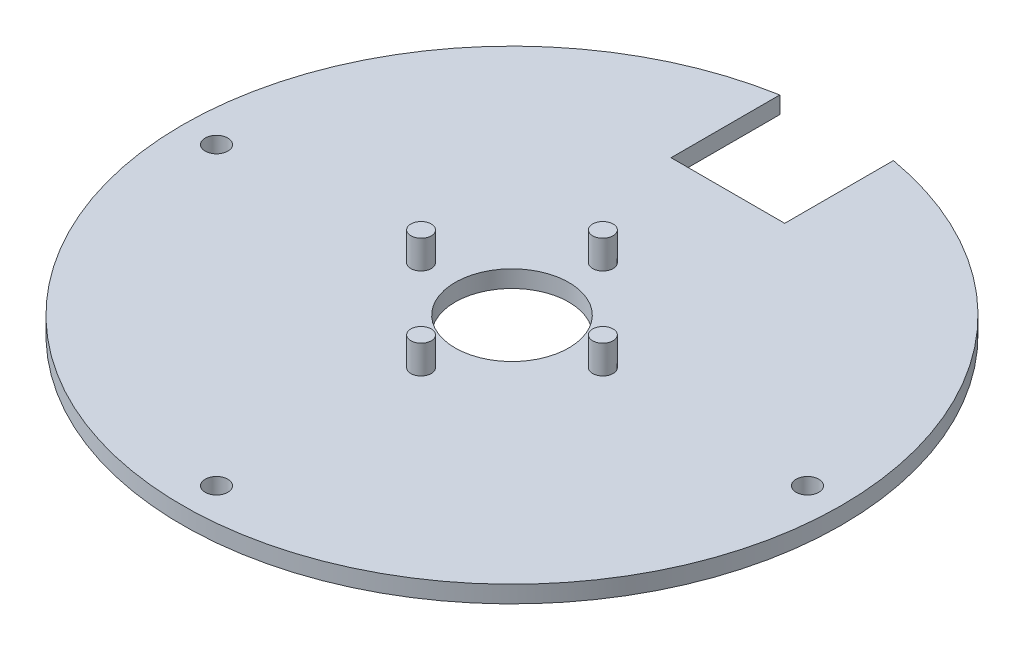
SolidWorks part; units mm, degrees
ref_plane "Front Plane" through (0, 0, 0) normal (0, 0, 1) x (1, 0, 0)
ref_plane "Top Plane" through (0, 0, 0) normal (0, 1, 0) x (1, 0, 0)
ref_plane "Right Plane" through (0, 0, 0) normal (1, 0, 0) x (0, 0, -1)
sketch "Sketch1" plane through (0, 0, 0) normal (0, 1, 0) x (1, 0, 0)
  circle A0 centre (0, 0) radius 29
extrude "Boss-Extrude1" add sketch "Sketch1" along normal blind 5 contours A0
sketch "Sketch3" plane through (0, 5, 0) normal (0, 1, 0) x (1, 0, 0)
  line L1 (-6.5, 29) -> (6.5, 29)
  line L2 (-6.5, 29) -> (-6.5, 18)
  line L3 (6.5, 29) -> (6.5, 18)
  line L4 (-6.5, 18) -> (6.5, 18)
  point P8 (0, 29)
sketch "Sketch4" plane through (0, 5, 0) normal (0, 1, 0) x (1, 0, 0)
  circle A0 centre (8, 0) radius 0.9
  circle A1 centre (-8, 0) radius 0.9
  circle A2 centre (0, 8) radius 0.9
  circle A3 centre (0, -8) radius 0.9
extrude "Boss-Extrude2" add sketch "Sketch4" along normal blind 2.5
sketch "Sketch5" plane through (0, 5, 0) normal (0, 1, 0) x (1, 0, 0)
  circle A2 centre (-20, 0) radius 1
  circle A3 centre (20, 0) radius 1
  circle A4 centre (0, -20) radius 1
sketch "Sketch6" plane through (0, 0, 0) normal (0, -1, 0) x (-1, 0, 0)
  circle A1 centre (0, 0) radius 29
sketch "Sketch7" plane through (0, 5, 0) normal (0, 1, 0) x (1, 0, 0)
  circle A0 centre (0, 0) radius 5
extrude "Cut-Extrude4" cut sketch "Sketch7" against normal blind 5
ref_plane "Plane1" through (6.5, 5, -28.2622) normal (-0.9746, 0, -0.2241) x (-0.2241, 0, 0.9746)
sketch "Sketch10" plane through (0, 5, 0) normal (0, 1, 0) x (1, 0, 0)
  circle A0 centre (0, 0) radius 29
sketch "Sketch11" plane through (0, 5, 0) normal (0, 1, 0) x (1, 0, 0)
  circle A0 centre (-26, 0) radius 1
  circle A1 centre (0, -26) radius 1
  circle A2 centre (26, 0) radius 1
extrude "Cut-Extrude6" cut sketch "Sketch11" against normal blind 5
sketch "Sketch12" plane through (0, 0, 0) normal (0, -1, 0) x (-1, 0, 0)
  circle A0 centre (0, 0) radius 29
extrude "Cut-Extrude7" cut sketch "Sketch12" against normal blind 1
sketch "Sketch13" plane through (0, 5, 0) normal (0, 1, 0) x (1, 0, 0)
  line L1 (-5, 29) -> (5, 29)
  line L6 (-5, 29) -> (-5, 19)
  line L7 (-5, 19) -> (5, 19)
  line L8 (5, 19) -> (5, 29)
  point P10 (0, 29)
extrude "Cut-Extrude8" cut sketch "Sketch13" against normal blind 10
sketch "Sketch14" plane through (0, 1, 0) normal (0, -1, 0) x (-1, 0, 0)
  circle A0 centre (0, 0) radius 29
extrude "Cut-Extrude9" cut sketch "Sketch14" against normal blind 2.5
